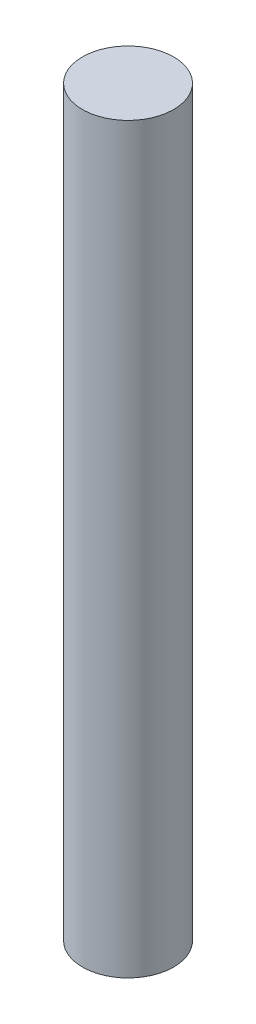
SolidWorks part; units mm, degrees
ref_plane "Front Plane" through (0, 0, 0) normal (0, 0, 1) x (1, 0, 0)
ref_plane "Top Plane" through (0, 0, 0) normal (0, 1, 0) x (1, 0, 0)
ref_plane "Right Plane" through (0, 0, 0) normal (1, 0, 0) x (0, 0, -1)
sketch "Sketch1" plane through (0, 0, 0) normal (0, 1, 0) x (1, 0, 0)
  circle A0 centre (0, 0) radius 3.5
  dimension "D1" = 7
extrude "Boss-Extrude1" add sketch "Sketch1" along normal blind 57
